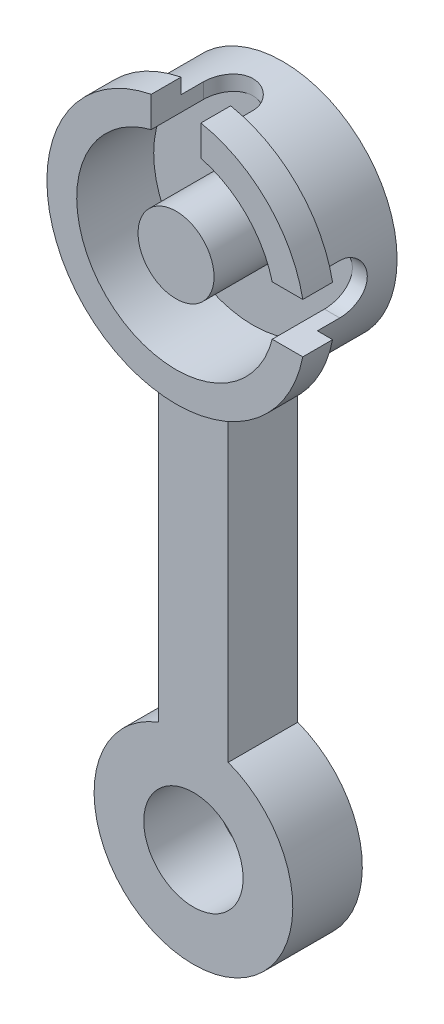
SolidWorks part; units mm, degrees
ref_plane "Alzado" through (0, 0, 0) normal (0, 0, 1) x (1, 0, 0)
ref_plane "Planta" through (0, 0, 0) normal (0, 1, 0) x (1, 0, 0)
ref_plane "Vista lateral" through (0, 0, 0) normal (1, 0, 0) x (0, 0, -1)
sketch "Croquis1" plane through (0, 0, 0) normal (0, 0, 1) x (1, 0, 0)
  circle A0 centre (0, 0) radius 10
  dimension "D1" = 20
extrude "Saliente-Extruir1" add sketch "Croquis1" along normal blind 3
sketch "Croquis2" plane through (0, 0, 3) normal (0, 0, 1) x (1, 0, 0)
  circle A0 centre (0, 0) radius 2.5
  circle A1 centre (0, 0) radius 4
  circle A2 centre (0, 0) radius 11.5
  circle A3 centre (0, 0) radius 10
  circle M1 centre (0, 0) radius 10
  dimension "D1" = 5
  dimension "D2" = 8
  dimension "D3" = 23
extrude "Saliente-Extruir3" add sketch "Croquis2" along normal blind 8 separate body contours A2 M1
sketch "Croquis3" plane through (0, 0, 3) normal (0, 0, -1) x (-1, 0, 0)
  circle A0 centre (0, 0) radius 11.5
  circle A1 centre (0, 0) radius 10
extrude "Saliente-Extruir4" add sketch "Croquis3" along normal up to surface (3 mm away) up to face at (10, 0, 0)
ref_plane "Plano1" through (0, 11.5, 0) normal (0, 1, 0) x (1, 0, 0)
sketch "Croquis7" plane through (0, 0, 11) normal (0, 0, 1) x (1, 0, 0)
  line L0 (0, 11.5) -> (0, 0) construction
  line L1 (4.2625, 11.5) -> (-4.2625, 11.5) construction
  line L2 (0, 0) -> (12.9867, 0) construction
  line L3 (0, 11.5) -> (-2.5, 11.5)
  line L4 (0, 11.5) -> (2.5, 11.5)
  line L5 (12.9867, 0) -> (12.9867, 2.5)
  line L6 (-2.5, 11.5) -> (2.5, 11.5)
  line L7 (-2.5, 11.5) -> (-2.5, 13.9876)
  line L8 (-2.5, 13.9876) -> (2.5, 13.9876)
  line L9 (2.5, 11.5) -> (2.5, 13.9876)
  line L10 (12.9867, 0) -> (12.9867, -2.5)
  line L11 (12.9867, 2.5) -> (14.6386, 2.5)
  line L16 (14.6386, 2.5) -> (14.6386, -2.5)
  line L17 (14.6386, -2.5) -> (12.9867, -2.5)
  dimension "D1" = 2.5
  dimension "D2" = 2.5
  dimension "D3" = 2.5
  dimension "D4" = 2.5
ref_plane "Plano2" through (0, 11.5, 0) normal (0, 1, 0) x (1, 0, 0)
ref_plane "Plano3" through (0, 11.5, 0) normal (0, 1, 0) x (1, 0, 0)
ref_plane "Plano4" through (-11.5, 0, 0) normal (-1, 0, 0) x (0, 0, 1)
sketch "Croquis12" plane through (0, 0, 3) normal (0, 0, 1) x (1, 0, 0)
  line L0 (0, 0) -> (0, -11.5) construction
  line L1 (0, -11.5) -> (-2.5, -11.5)
  line L2 (0, -11.5) -> (2.5, -11.5)
  line L3 (-2.5, -11.5) -> (-2.5, -10.878)
  line L4 (-2.5, -11.5) -> (2.5, -11.5)
  line L5 (-2.5, -11.5) -> (-2.5, -61.5)
  line L6 (-2.5, -61.5) -> (2.5, -61.5)
  line L7 (2.5, -11.5) -> (2.5, -61.5)
  line L8 (-2.5, -10.878) -> (0, -10.878)
  line L9 (0, -10.878) -> (0, -11.5)
  line L10 (0, -10.878) -> (2.5, -10.878)
  line L11 (2.5, -10.878) -> (2.5, -11.5)
  circle A0 centre (0, 0) radius 11.5 construction
  dimension "D1" = 2.5
  dimension "D2" = 2.5
  dimension "D3" = 50
extrude "Saliente-Extruir6" add sketch "Croquis12" against normal up to surface (3 mm away) contours L9 L8 L3 L1 | L11 L10 L9 L2 | L7 L2 L1 L5 L6 up to face at (11.5, 0, 0)
sketch "Croquis13" plane through (0, 0, 3) normal (0, 0, 1) x (1, 0, 0)
  line L1 (-2.5, -11.225) -> (2.5, -11.225)
  line L2 (-2.5, -11.225) -> (-2.5, -61.5)
  line L3 (-2.5, -61.5) -> (2.5, -61.5)
  line L4 (2.5, -11.225) -> (2.5, -61.5)
extrude "Saliente-Extruir7" add sketch "Croquis13" along normal up to surface (8 mm away) up to face at (10, 0, 11)
sketch "Croquis15" plane through (2.5, 0, 0) normal (1, 0, 0) x (0, 0, -1)
  line L0 (0, -11.225) -> (-11, -11.225) construction
  line L1 (-11, -61.5) -> (-9, -61.5)
  line L2 (-11, -61.5) -> (-11, -11.225)
  line L3 (-11, -11.225) -> (-9, -11.225)
  line L4 (-9, -61.5) -> (-9, -11.225)
  line L6 (0, -61.5) -> (-2, -61.5)
  line L7 (0, -61.5) -> (0, -11.225)
  line L8 (0, -11.225) -> (-2, -11.225)
  line L9 (-2, -61.5) -> (-2, -11.225)
  dimension "D1" = 2
  dimension "D2" = 2
extrude "Cortar-Extruir4" cut sketch "Croquis15" against normal blind 8
sketch "Croquis16" plane through (0, 0, 9) normal (0, 0, 1) x (1, 0, 0)
  line L0 (-2.5, -61.5) -> (-3.5, -61.5)
  line L1 (2.5, -61.5) -> (3.5, -61.5)
  line L2 (-3.5, -61.5) -> (-3.5, -10.233)
  line L3 (-3.5, -10.233) -> (3.5, -10.233)
  line L4 (3.5, -10.233) -> (3.5, -61.5)
  line L9 (-2.5, -61.5) -> (2.5, -61.5)
  line L10 (2.5, -61.5) -> (2.5, -11.225)
  line L11 (2.5, -11.225) -> (-2.5, -11.225)
  line L12 (-2.5, -11.225) -> (-2.5, -61.5)
  line L13 (-2.5, -61.5) -> (2.5, -61.5)
  dimension "D1" = 1
  dimension "D2" = 1
  dimension "D3" = 0
extrude "Saliente-Extruir8" add sketch "Croquis16" against normal up to surface (7 mm away) up to face at (0, -36.3625, 2)
sketch "Croquis21" plane through (0, 0, 2) normal (0, 0, -1) x (-1, 0, 0)
  line L0 (0, -11.225) -> (0, -52.725) construction
  line L1 (2.5, -11.225) -> (-2.5, -11.225) construction
  circle A0 centre (0, -52.725) radius 10
  dimension "D2" = 20
  dimension "D1" = 41.5
extrude "Saliente-Extruir9" add sketch "Croquis21" against normal up to surface (7 mm away) up to face at (0, -27.8969, 9)
sketch "Croquis22" plane through (0, 0, 2) normal (0, 0, -1) x (-1, 0, 0)
  circle A0 centre (0, -52.725) radius 5
  dimension "D1" = 10
extrude "Cortar-Extruir5" cut sketch "Croquis22" against normal blind 30
sketch "Croquis23" plane through (0, 0, 11) normal (0, 0, 1) x (1, 0, 0)
  line L0 (-2.5, -11.225) -> (2.5, -11.225) construction
  line L1 (-2.5, -11.225) -> (2.5, -11.225)
  arc A0 (2.5, -11.225) -> (-2.5, -11.225) centre (0, 0) ccw construction
  arc A1 (2.5, -11.225) -> (-2.5, -11.225) centre (0, 0) ccw
  circle A2 centre (0, 0) radius 10 construction
  circle A3 centre (0, 0) radius 10
extrude "Saliente-Extruir10" add sketch "Croquis23" along normal blind 1.25
sketch "Croquis24" plane through (0, 0, 12.25) normal (0, 0, 1) x (1, 0, 0)
  line L0 (-2.5, -11.225) -> (2.5, -11.225) construction
  line L1 (-2.5, -11.225) -> (2.5, -11.225)
  circle A0 centre (0, 0) radius 10 construction
  arc A1 (2.5, -11.225) -> (-2.5, -11.225) centre (0, 0) ccw construction
  circle A2 centre (0, 0) radius 10
  arc A3 (2.5, -11.225) -> (-2.5, -11.225) centre (0, 0) ccw
extrude "Cortar-Extruir6" cut sketch "Croquis24" against normal blind 1.5
sketch "Croquis25" plane through (0, 0, 10.75) normal (0, 0, 1) x (1, 0, 0)
  circle A0 centre (0, 0) radius 13
  arc A1 (2.5, -11.225) -> (-2.5, -11.225) centre (0, 0) ccw construction
  arc A2 (2.5, -11.225) -> (-2.5, -11.225) centre (0, 0) ccw
  arc M2 (2.5, -11.225) -> (-2.5, -11.225) centre (0, 0) ccw
  line M3 (-2.5, -11.225) -> (2.5, -11.225)
  dimension "D1" = 26
  dimension "D2" = 23
extrude "Saliente-Extruir11" add sketch "Croquis25" against normal blind 3 contours A0 M2 M3
sketch "Croquis30" plane through (0, 0, 3) normal (0, 0, 1) x (1, 0, 0)
  circle A0 centre (0, 0) radius 10
extrude "Cortar-Extruir14" cut sketch "Croquis30" against normal blind 10
sketch "Croquis31" plane through (0, 0, 0) normal (0, 0, -1) x (-1, 0, 0)
  circle A0 centre (0, 0) radius 11.5
  circle A1 centre (0, 0) radius 10 construction
  circle A2 centre (0, 0) radius 10
extrude "Saliente-Extruir12" add sketch "Croquis31" against normal up to surface (7.75 mm away) up to face at (0, 0.2564, 7.75)
sketch "Croquis32" plane through (0, 0, 0) normal (0, 0, -1) x (-1, 0, 0)
  circle A0 centre (0, 0) radius 10
extrude "Saliente-Extruir13" add sketch "Croquis32" against normal up to surface (10.75 mm away) up to face at (10, 0, 10.75)
sketch "Croquis33" plane through (0, 0, 0) normal (0, 0, -1) x (-1, 0, 0)
  circle A0 centre (0, 0) radius 11.5
sketch "Croquis34" plane through (0, 0, 10.75) normal (0, 0, 1) x (1, 0, 0)
  circle A0 centre (0, 0) radius 10
  dimension "D1" = 20
extrude "Cortar-Extruir15" cut sketch "Croquis34" against normal blind 7.75
sketch "Croquis36" plane through (0, 0, 3) normal (0, 0, 1) x (1, 0, 0)
  circle A0 centre (0, 0) radius 3.825
  dimension "D1" = 7.65
extrude "Saliente-Extruir14" add sketch "Croquis36" along normal up to surface (7.75 mm away) up to face at (10, 0, 10.75)
sketch "Croquis37" plane through (0, 0, 10.75) normal (0, 0, 1) x (1, 0, 0)
  circle A0 centre (0, 0) radius 3.825
sketch "Croquis39" plane through (0, 0, 0) normal (0, 0, -1) x (-1, 0, 0)
sketch "Croquis40" plane through (0, 11.5, 0) normal (0, 1, 0) x (1, 0, 0)
  line L0 (-13, -10.75) -> (13, -10.75) construction
  line L1 (0, -10.75) -> (0, -4.7931)
  line L2 (0, -10.75) -> (0, -5.5) construction
  line L3 (-2.5, -10.75) -> (-2.5, -5.5)
  line L4 (2.5, -10.75) -> (2.5, -5.5)
  line L6 (-2.5, -10.75) -> (2.5, -10.75)
  line L7 (0, -3) -> (0, 0) construction
  arc A0 (-2.5, -10.75) -> (2.5, -10.75) centre (0, -10.75) ccw
  arc A1 (2.5, -5.5) -> (-2.5, -5.5) centre (0, -5.5) ccw
  point P7 (0, -8.125)
  dimension "D2" = 2.5
  dimension "D1" = 5.5
extrude "Cortar-Extruir17" cut sketch "Croquis40" against normal blind 5.5 and the other way through all
extrude "Saliente-Extruir20" add sketch "Croquis7" against normal blind 9.5 contours L17 L16 L11 L5 L10
sketch "Croquis42" plane through (0, 0, 11) normal (0, 0, 1) x (1, 0, 0)
  line L1 (12.9867, 2.5) -> (14.6386, 2.5)
  line L2 (12.9867, 2.5) -> (12.9867, -2.5)
  line L3 (12.9867, -2.5) -> (14.6386, -2.5)
  line L4 (14.6386, 2.5) -> (14.6386, -2.5)
extrude "Cortar-Extruir18" cut sketch "Croquis42" against normal up to surface (0.25 mm away) up to face at (2.3915, 1.8463, 10.75)
sketch "Croquis43" plane through (14.6386, 0, 0) normal (1, 0, 0) x (0, 0, -1)
  line L0 (-10.75, 0) -> (-5.5, 0) construction
  line L1 (-10.75, 3.825) -> (-10.75, -3.825) construction
  line L2 (-10.75, 2.5) -> (-5.5, 2.5)
  line L3 (-10.75, -2.5) -> (-5.5, -2.5)
  line L4 (-3, 0) -> (0, 0) construction
  line L6 (-10.75, 2.5) -> (-10.75, -2.5)
  arc A0 (-10.75, 2.5) -> (-10.75, -2.5) centre (-10.75, 0) ccw
  arc A1 (-5.5, -2.5) -> (-5.5, 2.5) centre (-5.5, 0) ccw
  point P5 (-8.125, 0)
  line M3 (-10.75, -2.5) -> (-1.5, -2.5)
  line M4 (-1.5, -2.5) -> (-1.5, 2.5)
  line M5 (-1.5, 2.5) -> (-10.75, 2.5)
  dimension "D2" = 2.5
  dimension "D1" = 3
extrude "Cortar-Extruir19" cut sketch "Croquis43" against normal up to surface (3.4137 mm away) contours A1 M3 M4 M5
sketch "Croquis44" plane through (14.6386, 0, 0) normal (1, 0, 0) x (0, 0, -1)
  line L3 (-5.5, 2.5) -> (-10.75, 2.5)
  line L4 (-10.75, 2.5) -> (-10.75, -2.5)
  line L5 (-10.75, -2.5) -> (-5.5, -2.5)
  line L6 (-5.5, 2.5) -> (-10.75, 2.5)
  line L7 (-10.75, 2.5) -> (-10.75, -2.5)
  line L8 (-10.75, -2.5) -> (-5.5, -2.5)
  arc A1 (-5.5, -2.5) -> (-5.5, 2.5) centre (-5.5, 0) ccw
  arc A2 (-5.5, -2.5) -> (-5.5, 2.5) centre (-5.5, 0) ccw
  dimension "D1" = 0
extrude "Cortar-Extruir20" cut sketch "Croquis44" against normal up to surface (4.9562 mm away)
